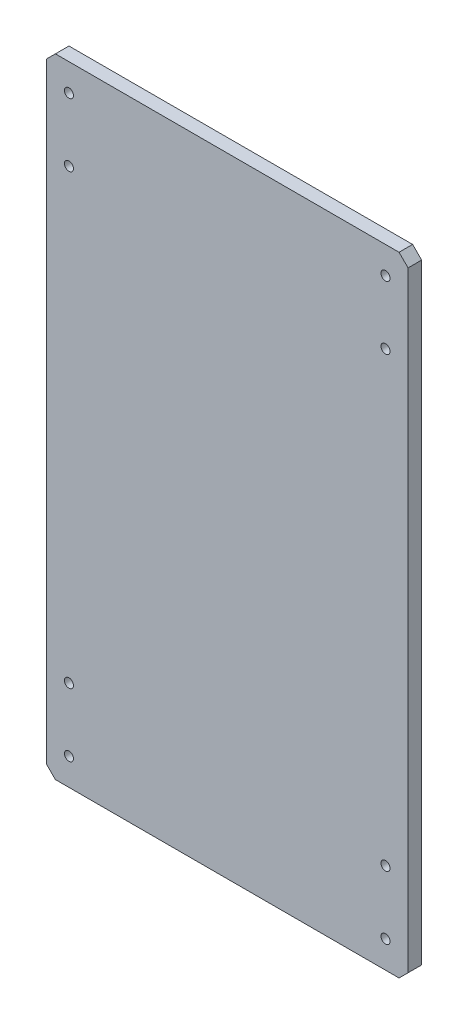
SolidWorks part; units mm, degrees
ref_plane "Front Plane" through (0, 0, 0) normal (0, 0, 1) x (1, 0, 0)
ref_plane "Top Plane" through (0, 0, 0) normal (0, 1, 0) x (1, 0, 0)
ref_plane "Right Plane" through (0, 0, 0) normal (1, 0, 0) x (0, 0, -1)
ref_plane "Plane1" through (0, 0, 3) normal (0, 0, 1) x (1, 0, 0)
sketch "Sketch1" plane through (0, 0, 3) normal (0, 0, 1) x (1, 0, 0)
  line L0 (-38, -69.5) -> (38, -69.5)
  line L1 (38, -69.5) -> (40, -67.5)
  line L2 (40, -67.5) -> (40, 67.5)
  line L3 (40, 67.5) -> (38, 69.5)
  line L4 (38, 69.5) -> (-38, 69.5)
  line L5 (-38, 69.5) -> (-40, 67.5)
  line L6 (-40, 67.5) -> (-40, -67.5)
  line L7 (-40, -67.5) -> (-38, -69.5)
  circle A0 centre (35, 49.5) radius 1
  circle A1 centre (-35, -63.5) radius 1
  circle A2 centre (35, 63.5) radius 1
  circle A3 centre (-35, -49.5) radius 1
  circle A4 centre (-35, 49.5) radius 1
  circle A5 centre (-35, 63.5) radius 1
  circle A6 centre (35, -49.5) radius 1
  circle A7 centre (35, -63.5) radius 1
extrude "Boss-Extrude1" add sketch "Sketch1" against normal blind 3
